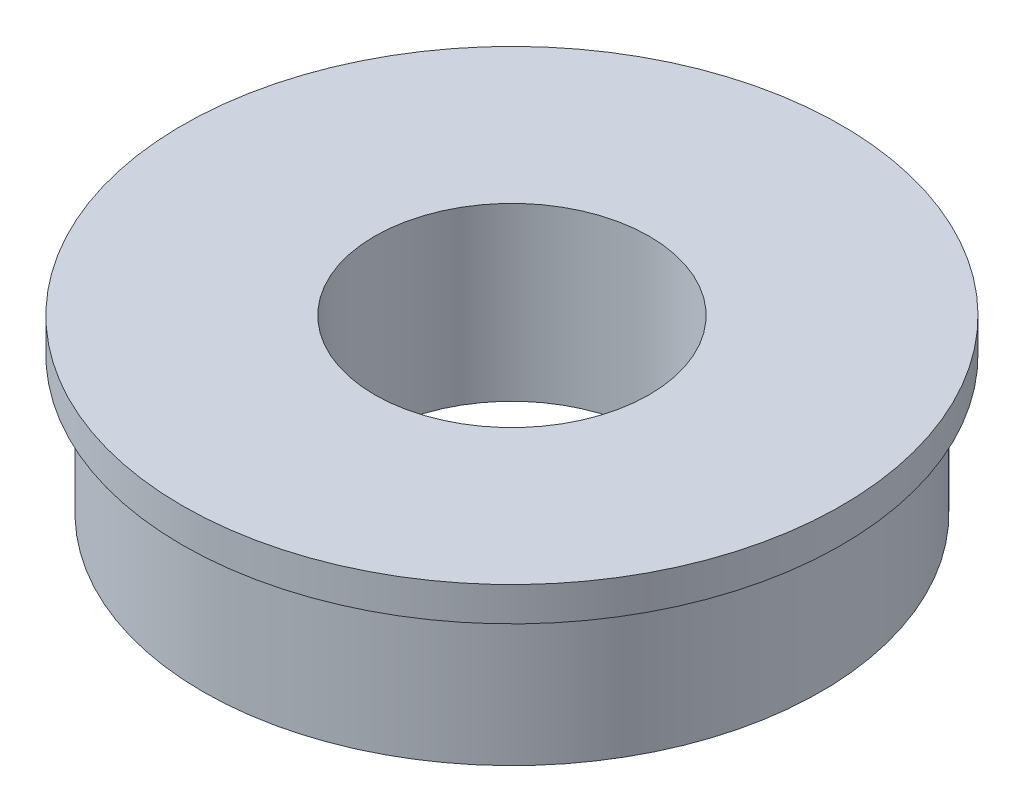
SolidWorks part; units mm, degrees
ref_plane "Front Plane" through (0, 0, 0) normal (0, 0, 1) x (1, 0, 0)
ref_plane "Top Plane" through (0, 0, 0) normal (0, 1, 0) x (1, 0, 0)
ref_plane "Right Plane" through (0, 0, 0) normal (1, 0, 0) x (0, 0, -1)
sketch "Sketch1" plane through (0, 0, 0) normal (0, 1, 0) x (1, 0, 0)
  circle A0 centre (0, 0) radius 6.35
  circle A1 centre (0, 0) radius 14.2875
  dimension "D1" = 12.7
  dimension "D2" = 28.575
extrude "Boss-Extrude1" add sketch "Sketch1" along normal blind 6.35
sketch "Sketch2" plane through (0, 6.35, 0) normal (0, 1, 0) x (1, 0, 0)
  circle A0 centre (0, 0) radius 15.24
  circle A1 centre (0, 0) radius 6.35
  dimension "D1" = 30.48
extrude "Boss-Extrude2" add sketch "Sketch2" along normal blind 1.5748
equation "\"D1@Boss-Extrude1\"=0.312-0.062"
